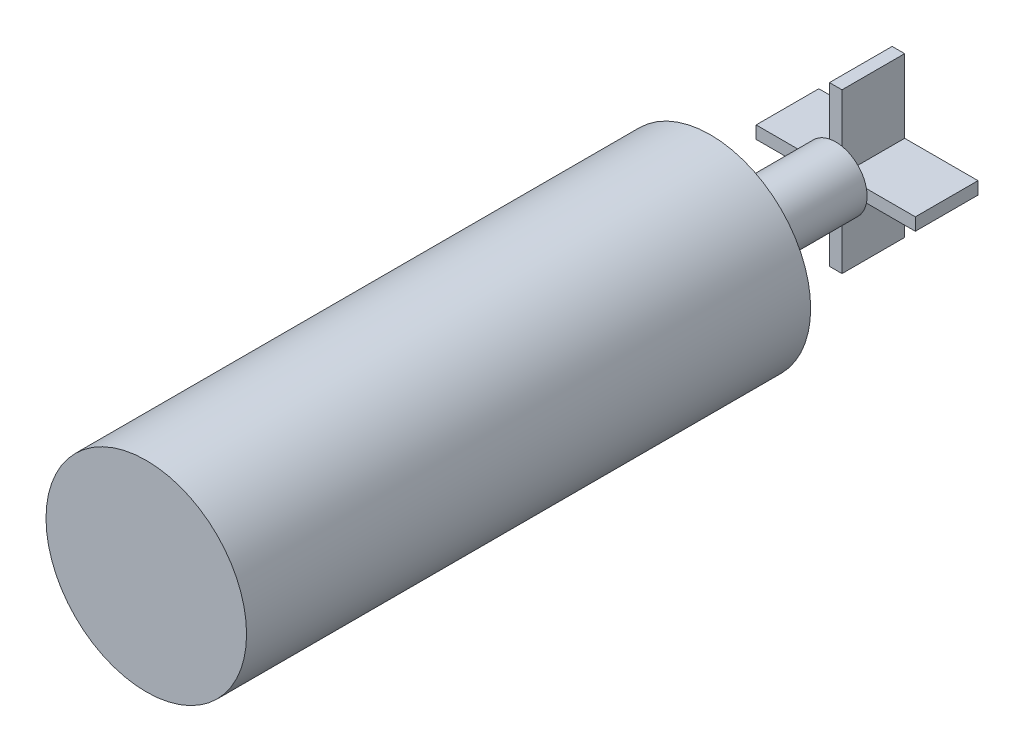
SolidWorks part; units mm, degrees
ref_plane "Front Plane" through (0, 0, 0) normal (0, 0, 1) x (1, 0, 0)
ref_plane "Top Plane" through (0, 0, 0) normal (0, 1, 0) x (1, 0, 0)
ref_plane "Right Plane" through (0, 0, 0) normal (1, 0, 0) x (0, 0, -1)
sketch "Sketch2" plane through (0, 0, 0) normal (0, 0, 1) x (1, 0, 0)
  circle A0 centre (0, 0) radius 16
  dimension "D1" = 32
extrude "Boss-Extrude1" add sketch "Sketch2" along normal blind 90
sketch "Sketch3" plane through (0, 0, 0) normal (0, 0, -1) x (-1, 0, 0)
  circle A0 centre (0, 0) radius 5
  dimension "D1" = 10
extrude "Boss-Extrude2" add sketch "Sketch3" along normal blind 20
sketch "Sketch4" plane through (0, 0, -20) normal (0, 0, -1) x (-1, 0, 0)
  circle A0 centre (0, 0) radius 15.25
  dimension "D1" = 30.5
extrude "Boss-Extrude3" [suppressed] add sketch "Sketch4" along normal blind 2
sketch "Sketch5" plane through (0, 0, -20) normal (0, 0, -1) x (-1, 0, 0)
  line L0 (1, 1) -> (12.7, 1)
  line L1 (-12.7, 1) -> (-1, 1)
  line L2 (-12.7, 1) -> (-12.7, -1)
  line L3 (-12.7, -1) -> (-1, -1)
  line L4 (12.7, 1) -> (12.7, -1)
  line L5 (-12.7, 1) -> (12.7, -1) construction
  line L6 (-12.7, -1) -> (12.7, 1) construction
  line L7 (-1, 12.7) -> (1, 12.7)
  line L8 (-1, 12.7) -> (-1, 1)
  line L9 (-1, -12.7) -> (1, -12.7)
  line L10 (1, 12.7) -> (1, 1)
  line L11 (-1, 12.7) -> (1, -12.7) construction
  line L12 (-1, -12.7) -> (1, 12.7) construction
  line L13 (-1, -1) -> (-1, -12.7)
  line L14 (1, -1) -> (1, -12.7)
  line L15 (1, -1) -> (12.7, -1)
  point P0 (0, 0)
  point P6 (0, 0)
  dimension "D1" = 25.4
  dimension "D2" = 2
extrude "Boss-Extrude4" add sketch "Sketch5" along normal blind 10
